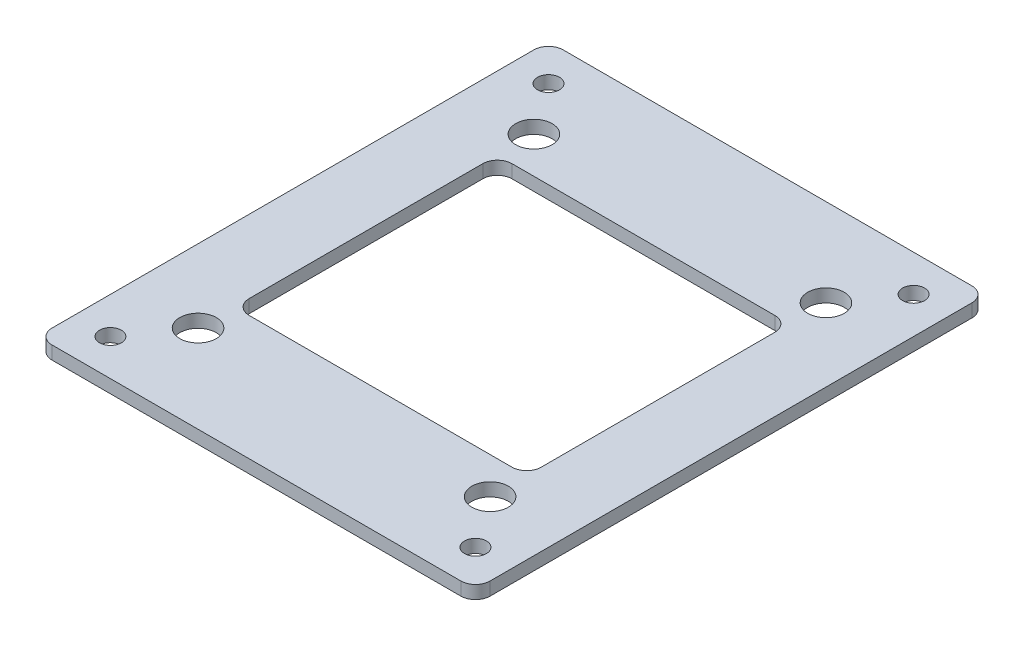
SolidWorks part; units mm, degrees
ref_plane "前视基准面" through (0, 0, 0) normal (0, 0, 1) x (1, 0, 0)
ref_plane "上视基准面" through (0, 0, 0) normal (0, 1, 0) x (1, 0, 0)
ref_plane "右视基准面" through (0, 0, 0) normal (1, 0, 0) x (0, 0, -1)
other "Configuration Table"
sketch "草图1" plane through (0, 0, 0) normal (0, 1, 0) x (1, 0, 0)
  line L1 (-30, -35) -> (30, -35)
  line L2 (-30, -35) -> (-30, 35)
  line L3 (-30, 35) -> (30, 35)
  line L4 (30, -35) -> (30, 35)
  line L5 (0, 35) -> (0, -35) construction
  line L6 (-30, 0) -> (30, 0) construction
  circle A0 centre (-20, 23) radius 2.5
  circle A1 centre (20, 23) radius 2.5
  circle A2 centre (20, -23) radius 2.5
  circle A3 centre (-20, -23) radius 2.5
  point P0 (0, 0)
  dimension "D3" = 5
  dimension "D4" = 23
  dimension "D5" = 20
  dimension "D1" = 60
  dimension "D2" = 70
extrude "凸台-拉伸1" add sketch "草图1" along normal blind 1.8
sketch "草图2" plane through (0, 1.8, 0) normal (0, 1, 0) x (1, 0, 0)
  line L0 (-1000, 0) -> (49000, 0) construction
  line L1 (0, -1000) -> (0, 49000) construction
  line L3 (-20, -18) -> (20, -18)
  line L4 (-20, -18) -> (-20, 18)
  line L5 (-20, 18) -> (20, 18)
  line L6 (20, -18) -> (20, 18)
  line L7 (0, 18) -> (0, -18) construction
  line L8 (-20, 0) -> (20, 0) construction
  circle A0 centre (-25, 30) radius 1.5
  circle A1 centre (25, 30) radius 1.5
  circle A2 centre (25, -30) radius 1.5
  circle A3 centre (-25, -30) radius 1.5
  point P13 (0, 0)
  dimension "D1" = 3
  dimension "D2" = 30
  dimension "D3" = 25
  dimension "D4" = 36
  dimension "D5" = 40
extrude "切除-拉伸1" cut sketch "草图2" against normal through all
fillet "圆角1" radius 2 8 edges at (20, 0.9, -18) (-20, 0.9, -18) (20, 0.9, 18) (-20, 0.9, 18) (-30, 0.9, 35) (30, 0.9, 35) (30, 0.9, -35) (-30, 0.9, -35)
